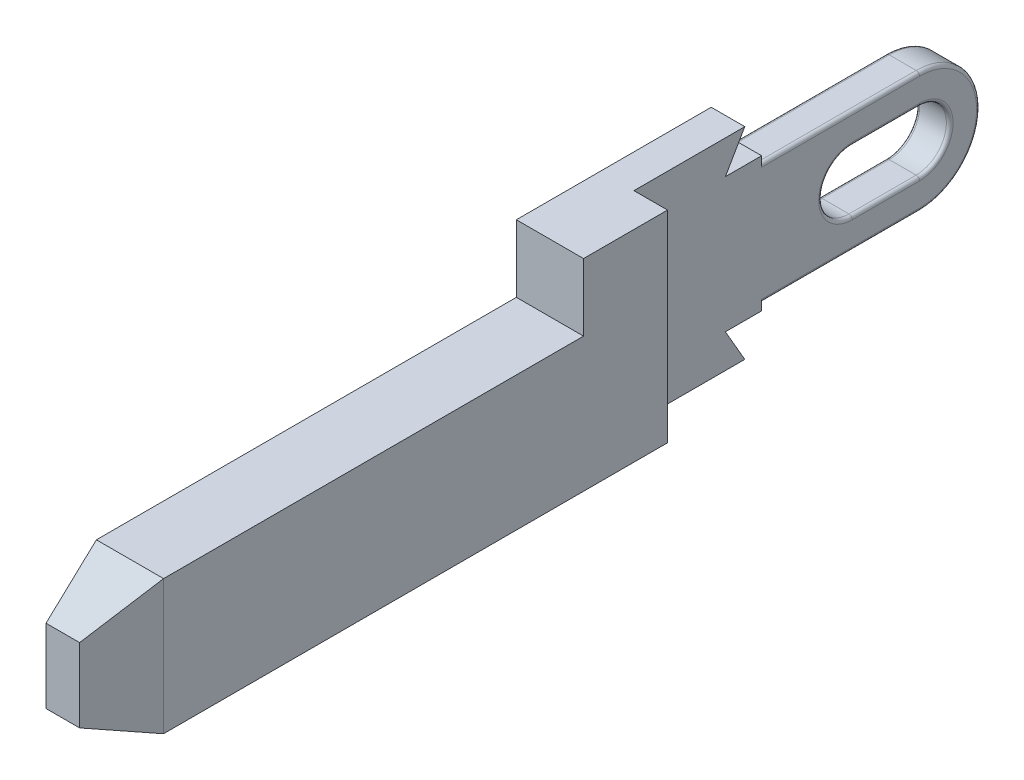
SolidWorks part; units mm, degrees
ref_plane "Спереди" through (0, 0, 0) normal (0, 0, 1) x (1, 0, 0)
ref_plane "Сверху" through (0, 0, 0) normal (0, 1, 0) x (1, 0, 0)
ref_plane "Справа" through (0, 0, 0) normal (1, 0, 0) x (0, 0, -1)
sketch "Эскиз1" plane through (0, 0, 0) normal (1, 0, 0) x (0, 0, -1)
  line L0 (0, 0) -> (14.6296, 0) construction
  line L1 (0, 0) -> (0, 1.1)
  line L2 (0, 1.1) -> (2, 2)
  line L3 (2, 2) -> (14.5, 2)
  line L4 (14.5, 2) -> (14.5, 4)
  line L5 (14.5, 4) -> (20.3, 4)
  line L6 (25.5, 1) -> (23.5, 1) construction
  line L7 (23.5, 1.9) -> (25.5, 1.9)
  line L8 (20.3, 4) -> (19.7226, 3)
  line L9 (20.8, 2.8) -> (25.5, 2.8)
  line L10 (0, 0) -> (0, -1.1)
  line L11 (0, -1.1) -> (2, -2)
  line L12 (2, -2) -> (20.3, -2)
  line L13 (23.5, 0.1) -> (25.5, 0.1)
  line L14 (19.7226, 3) -> (20.8, 3)
  line L15 (20.3, -2) -> (19.7226, -1)
  line L16 (20.8, -0.8) -> (25.5, -0.8)
  line L17 (20.8, 3) -> (20.8, 2.8)
  line L18 (19.7226, -1) -> (20.8, -1)
  line L19 (20.8, -1) -> (20.8, -0.8)
  arc A0 (25.5, 2.8) -> (25.5, -0.8) centre (25.5, 1) cw
  arc A1 (25.5, 0.1) -> (25.5, 1.9) centre (25.5, 1) ccw
  arc A2 (23.5, 1.9) -> (23.5, 0.1) centre (23.5, 1) ccw
  point P9 (27.3, 1)
  dimension "D15" = 1.8
  dimension "D16" = 7
  dimension "D17" = 1.8
  dimension "D18" = 1.8
  dimension "D19" = 2
  dimension "D1" = 4
  dimension "D2" = 2
  dimension "D3" = 2
  dimension "D4" = 2
  dimension "D5" = 2.2
  dimension "D6" = 1.1
  dimension "D7" = 14.5
  dimension "D8" = 6
  dimension "D9" = 5.8
  dimension "D10" = 3.6
  dimension "D11" = 60
  dimension "D12" = 1.2
  dimension "D13" = 5.8
  dimension "D14" = 60
  dimension "D20" = 1.8
  dimension "D21" = 0.5
  dimension "D22" = 0.5
  dimension "D23" = 4
  dimension "D24" = 0.2
extrude "Бобышка-Вытянуть1" add sketch "Эскиз1" along normal blind 2
sketch "Эскиз2" plane through (2, 0, 0) normal (1, 0, 0) x (0, 0, -1)
  line L0 (14.5, 4) -> (14.5, 2) construction
  line L1 (17, 5.6301) -> (29.2441, 5.6301)
  line L2 (17, 5.6301) -> (17, -3.3416)
  line L3 (17, -3.3416) -> (29.2441, -3.3416)
  line L4 (29.2441, 5.6301) -> (29.2441, -3.3416)
  dimension "D1" = 2.5
extrude "Вырез-Вытянуть1" cut sketch "Эскиз2" against normal blind 1
chamfer "Фаска1" distance 0.5 distance2 2 1 edges at (2, 0, 0)
chamfer "Фаска2" distance 2 distance2 0.5 1 edges at (0, 0, 0)
fillet "Скругление1" radius 0.1 14 edges at (1, -0.8, -23.15) (1, 1, -27.3) (1, 2.8, -23.15) (0, -0.8, -23.15) (0, 1, -27.3) (0, 2.8, -23.15) (1, 1, -22.6) (1, 1.9, -24.5) (1, 1, -26.4) (1, 0.1, -24.5) (0, 1, -22.6) (0, 1.9, -24.5) (0, 1, -26.4) (0, 0.1, -24.5)
